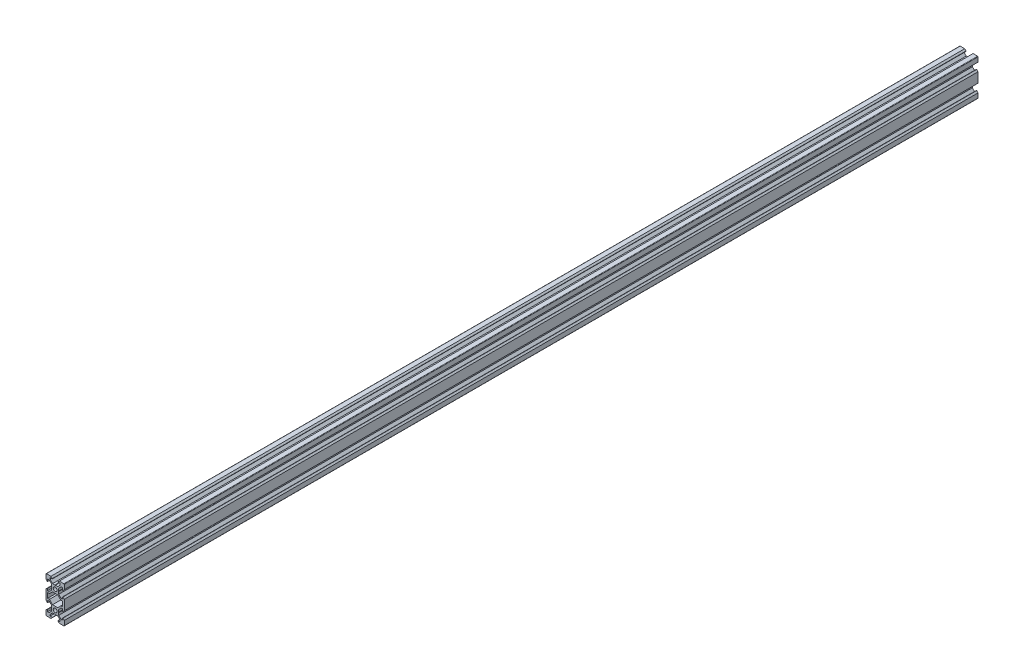
SolidWorks part; units mm, degrees
material "6061-T6 (SS)"
ref_plane "Front Plane" through (0, 0, 0) normal (0, 0, 1) x (1, 0, 0)
ref_plane "Top Plane" through (0, 0, 0) normal (0, 1, 0) x (1, 0, 0)
ref_plane "Right Plane" through (0, 0, 0) normal (1, 0, 0) x (0, 0, -1)
sketch "Sketch1" plane through (0, 0, 0) normal (0, 0, 1) x (1, 0, 0)
  line L0 (0, 0) -> (10, 0) construction
  line L1 (9.5, -20) -> (-9.5, -20)
  line L2 (10, -19.5) -> (10, 19.5)
  line L3 (9.5, 20) -> (-9.5, 20)
  line L4 (-10, -19.5) -> (-10, 19.5)
  line L5 (10, -20) -> (-10, 20) construction
  line L6 (10, 20) -> (-10, -20) construction
  circle A0 centre (0, 10) radius 2.1
  circle A1 centre (0, -10) radius 2.1
  arc A2 (-9.5, -20) -> (-10, -19.5) centre (-9.5, -19.5) cw
  arc A3 (9.5, -20) -> (10, -19.5) centre (9.5, -19.5) ccw
  arc A4 (10, 19.5) -> (9.5, 20) centre (9.5, 19.5) ccw
  arc A5 (-9.5, 20) -> (-10, 19.5) centre (-9.5, 19.5) ccw
  point P0 (0, 0)
  line B0 (0, 10) -> (0, 20) construction
  line B1 (0, 13.69) -> (-0.21, 13.9)
  line B2 (-0.21, 13.9) -> (-2.8393, 13.9)
  line B3 (-2.8393, 13.9) -> (-5.5, 16.5607)
  line B4 (-5.5, 16.5607) -> (-5.5, 18.2)
  line B5 (-5.5, 18.2) -> (-3.125, 18.2)
  line B6 (-3.125, 18.2) -> (-3.125, 18.545)
  line B7 (-3.125, 18.545) -> (-4.58, 20)
  line B8 (-4.58, 20) -> (4.58, 20)
  line B9 (0, 10) -> (-5.9132, 15.9132) construction
  line B10 (3.125, 18.545) -> (4.58, 20)
  line B11 (3.125, 18.2) -> (3.125, 18.545)
  line B12 (5.5, 18.2) -> (3.125, 18.2)
  line B13 (5.5, 16.5607) -> (5.5, 18.2)
  line B14 (2.8393, 13.9) -> (5.5, 16.5607)
  line B15 (0.21, 13.9) -> (2.8393, 13.9)
  line B16 (0, 13.69) -> (0.21, 13.9)
  line B17 (0, 10) -> (-10, 10) construction
  line B18 (-3.69, 10) -> (-3.9, 9.79)
  line B19 (-3.9, 9.79) -> (-3.9, 7.1607)
  line B20 (-3.9, 7.1607) -> (-6.5607, 4.5)
  line B21 (-6.5607, 4.5) -> (-8.2, 4.5)
  line B22 (-8.2, 4.5) -> (-8.2, 6.875)
  line B23 (-8.2, 6.875) -> (-8.545, 6.875)
  line B24 (-8.545, 6.875) -> (-10, 5.42)
  line B25 (-10, 5.42) -> (-10, 14.58)
  line B26 (0, 10) -> (-5.9132, 4.0868) construction
  line B27 (-8.545, 13.125) -> (-10, 14.58)
  line B28 (-8.2, 13.125) -> (-8.545, 13.125)
  line B29 (-8.2, 15.5) -> (-8.2, 13.125)
  line B30 (-6.5607, 15.5) -> (-8.2, 15.5)
  line B31 (-3.9, 12.8393) -> (-6.5607, 15.5)
  line B32 (-3.9, 10.21) -> (-3.9, 12.8393)
  line B33 (-3.69, 10) -> (-3.9, 10.21)
  line B34 (0, -10) -> (-10, -10) construction
  line B35 (-3.69, -10) -> (-3.9, -10.21)
  line B36 (-3.9, -10.21) -> (-3.9, -12.8393)
  line B37 (-3.9, -12.8393) -> (-6.5607, -15.5)
  line B38 (-6.5607, -15.5) -> (-8.2, -15.5)
  line B39 (-8.2, -15.5) -> (-8.2, -13.125)
  line B40 (-8.2, -13.125) -> (-8.545, -13.125)
  line B41 (-8.545, -13.125) -> (-10, -14.58)
  line B42 (-10, -14.58) -> (-10, -5.42)
  line B43 (0, -10) -> (-5.9132, -15.9132) construction
  line B44 (-8.545, -6.875) -> (-10, -5.42)
  line B45 (-8.2, -6.875) -> (-8.545, -6.875)
  line B46 (-8.2, -4.5) -> (-8.2, -6.875)
  line B47 (-6.5607, -4.5) -> (-8.2, -4.5)
  line B48 (-3.9, -7.1607) -> (-6.5607, -4.5)
  line B49 (-3.9, -9.79) -> (-3.9, -7.1607)
  line B50 (-3.69, -10) -> (-3.9, -9.79)
  line B51 (0, -10) -> (0, -20) construction
  line B52 (0, -13.69) -> (0.21, -13.9)
  line B53 (0.21, -13.9) -> (2.8393, -13.9)
  line B54 (2.8393, -13.9) -> (5.5, -16.5607)
  line B55 (5.5, -16.5607) -> (5.5, -18.2)
  line B56 (5.5, -18.2) -> (3.125, -18.2)
  line B57 (3.125, -18.2) -> (3.125, -18.545)
  line B58 (3.125, -18.545) -> (4.58, -20)
  line B59 (4.58, -20) -> (-4.58, -20)
  line B60 (0, -10) -> (5.9132, -15.9132) construction
  line B61 (-3.125, -18.545) -> (-4.58, -20)
  line B62 (-3.125, -18.2) -> (-3.125, -18.545)
  line B63 (-5.5, -18.2) -> (-3.125, -18.2)
  line B64 (-5.5, -16.5607) -> (-5.5, -18.2)
  line B65 (-2.8393, -13.9) -> (-5.5, -16.5607)
  line B66 (-0.21, -13.9) -> (-2.8393, -13.9)
  line B67 (0, -13.69) -> (-0.21, -13.9)
  line B68 (0, -10) -> (10, -10) construction
  line B69 (3.69, -10) -> (3.9, -9.79)
  line B70 (3.9, -9.79) -> (3.9, -7.1607)
  line B71 (3.9, -7.1607) -> (6.5607, -4.5)
  line B72 (6.5607, -4.5) -> (8.2, -4.5)
  line B73 (8.2, -4.5) -> (8.2, -6.875)
  line B74 (8.2, -6.875) -> (8.545, -6.875)
  line B75 (8.545, -6.875) -> (10, -5.42)
  line B76 (10, -5.42) -> (10, -14.58)
  line B77 (0, -10) -> (5.9132, -4.0868) construction
  line B78 (8.545, -13.125) -> (10, -14.58)
  line B79 (8.2, -13.125) -> (8.545, -13.125)
  line B80 (8.2, -15.5) -> (8.2, -13.125)
  line B81 (6.5607, -15.5) -> (8.2, -15.5)
  line B82 (3.9, -12.8393) -> (6.5607, -15.5)
  line B83 (3.9, -10.21) -> (3.9, -12.8393)
  line B84 (3.69, -10) -> (3.9, -10.21)
  line B85 (0, 10) -> (10, 10) construction
  line B86 (3.69, 10) -> (3.9, 10.21)
  line B87 (3.9, 10.21) -> (3.9, 12.8393)
  line B88 (3.9, 12.8393) -> (6.5607, 15.5)
  line B89 (6.5607, 15.5) -> (8.2, 15.5)
  line B90 (8.2, 15.5) -> (8.2, 13.125)
  line B91 (8.2, 13.125) -> (8.545, 13.125)
  line B92 (8.545, 13.125) -> (10, 14.58)
  line B93 (10, 14.58) -> (10, 5.42)
  line B94 (0, 10) -> (5.9132, 15.9132) construction
  line B95 (8.545, 6.875) -> (10, 5.42)
  line B96 (8.2, 6.875) -> (8.545, 6.875)
  line B97 (8.2, 4.5) -> (8.2, 6.875)
  line B98 (6.5607, 4.5) -> (8.2, 4.5)
  line B99 (3.9, 7.1607) -> (6.5607, 4.5)
  line B100 (3.9, 9.79) -> (3.9, 7.1607)
  line B101 (3.69, 10) -> (3.9, 9.79)
  line B102 (-8.2, -2.7) -> (-8.2, 2.7)
  line B103 (-8.2, 2.7) -> (-6.2393, 2.7)
  line B104 (-6.2393, 2.7) -> (-2.8393, 6.1)
  line B105 (-2.8393, 6.1) -> (2.8393, 6.1)
  line B106 (0, 6.1) -> (0, 0) construction
  line B107 (0, 0) -> (-8.2, 0) construction
  line B108 (6.2393, 2.7) -> (2.8393, 6.1)
  line B109 (8.2, 2.7) -> (6.2393, 2.7)
  line B110 (8.2, -2.7) -> (8.2, 2.7)
  line B111 (8.2, -2.7) -> (6.2393, -2.7)
  line B112 (6.2393, -2.7) -> (2.8393, -6.1)
  line B113 (-2.8393, -6.1) -> (2.8393, -6.1)
  line B114 (-6.2393, -2.7) -> (-2.8393, -6.1)
  line B115 (-8.2, -2.7) -> (-6.2393, -2.7)
  line B116 (0, 6.1) -> (0, 10) construction
  line B117 (0, 10) -> (-5.0927, 4.9073) construction
  dimension "D4" = 4.2
  dimension "D5" = 0.5
  dimension "D1" = 20
  dimension "D2" = 40
  dimension "D3" = 20
sketch_block_instance "V Slot 1-4"
sketch_block "V Slot 1" parameters "D1"=10, "D2"=11, "D3"=4.3, "D4"=1.8, "D5"=0.21, "D6"=45, "D7"=9.16, "D8"=1.5, "D9"=6.25
sketch_block_instance "V Slot 1-5"
sketch_block_instance "V Slot 1-6"
sketch_block_instance "V Slot 1-7"
sketch_block_instance "V Slot 1-8"
sketch_block_instance "V Slot 1-9"
sketch_block_instance "Center Cutout 1-1"
sketch_block "Center Cutout 1" parameters "D1"=5.4, "D2"=12.2, "D3"=8.2, "D4"=45, "D5"=10, "D6"=1.5
extrude "Boss-Extrude1" add sketch "Sketch1" along normal blind 1000 contours B101 B86 B87 B88 B89 B90 B91 B92 L2 A4 L3 B10 B11 B12 B13 B14 B15 B16 B1 B2 B3 B4 B5 B6 B7 A5 L4 B27 B28 B29 B30 B31 B32 B33 B18 B19 B20 B21 B22 B23 B24 B44 B45 B46 B47 B48 B49 B50 B35
ref_plane "Plane1" through (0, 0, 500) normal (0, 0, 1) x (1, 0, 0)
sketch "Sketch2" plane through (10, 0, 0) normal (1, 0, 0) x (0, 0, -1)
  line L0 (-500, 142.4792) -> (-500, -76.8773) construction
  line L1 (-1000, 19.5) -> (0, 19.5) construction
  line L2 (-168, -10) -> (-148, 10) construction
  line L3 (-168, 10) -> (-148, 10) construction
  line L4 (-168, 10) -> (-168, -10) construction
  line L5 (-168, -10) -> (-148, -10) construction
  line L6 (-148, 10) -> (-148, -10) construction
  line L7 (-158, 0) -> (0, 0) construction
  point P4 (-500, 19.5)
  dimension "D1" = 158
  dimension "D2" = 20
hole_wizard "M5 Clearance Hole1" positions "3DSketch3" profile "Sketch5" hole size "M5" standard "ANSI Metric" end condition through all
sketch3d "3DSketch3"
  line L0 (10, 10, 168) -> (10, -10, 168) construction
  line L1 (10, 10, 148) -> (10, -10, 148) construction
  point P0 (10, -10, 168)
  point P4 (10, 10, 168)
  point P6 (10, 10, 148)
  point P10 (10, -10, 148)
sketch "Sketch5" plane through (10, -10, 168) normal (0, 1, 0) x (0, 0, -1)
  line L0 (0, 0) -> (0, 20)
  line L1 (0, 20) -> (2.75, 20)
  line L2 (2.75, 20) -> (2.75, 0)
  line L5 (2.75, 0) -> (0, 0)
  line L11 (0, -6.35) -> (0, 107.95) construction
  dimension "Thru Hole Dia." = 5.5
  dimension "Thru Hole Depth" = 20
mirror "Mirror1" about plane through (0, 0, 500) normal (0, 0, 1) of "M5 Clearance Hole1"
